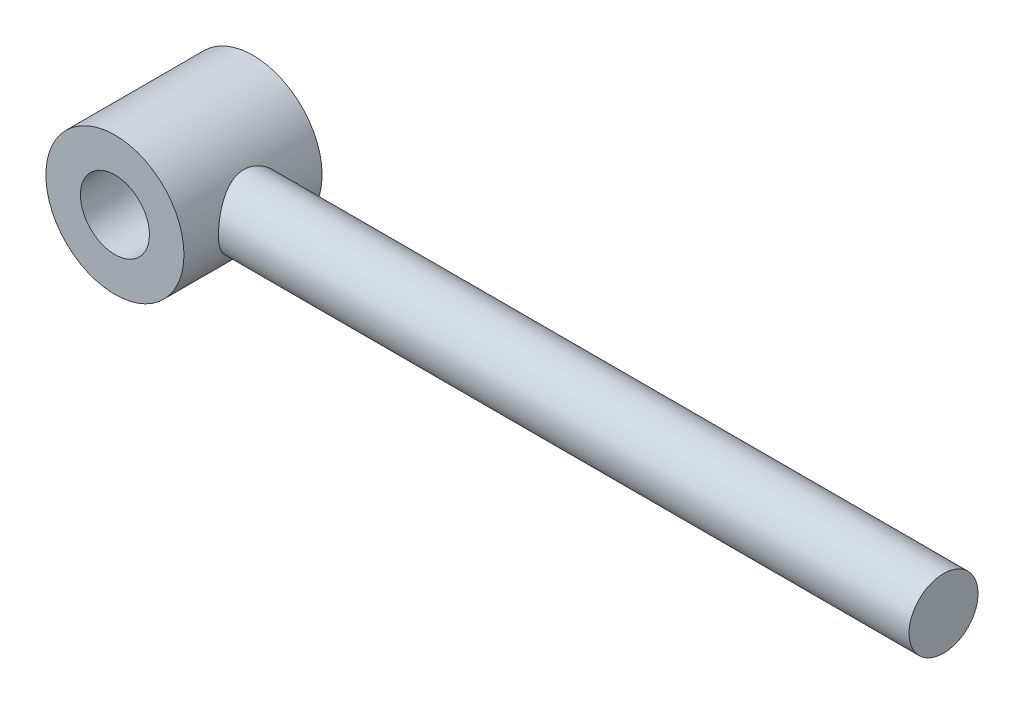
SolidWorks part; units mm, degrees
ref_plane "Piano frontale" through (0, 0, 0) normal (0, 0, 1) x (1, 0, 0)
ref_plane "Piano superiore" through (0, 0, 0) normal (0, 1, 0) x (1, 0, 0)
ref_plane "Piano destro" through (0, 0, 0) normal (1, 0, 0) x (0, 0, -1)
sketch "Schizzo1" plane through (0, 0, 0) normal (0, 0, 1) x (1, 0, 0)
  circle A0 centre (0, 0) radius 10
  circle A1 centre (0, 0) radius 5
  dimension "D1" = 20
  dimension "D2" = 10
extrude "Estrusione-Estrusione1" add sketch "Schizzo1" along normal blind 20
ref_plane "Piano1" through (110, 0, 0) normal (-1, 0, 0) x (0, 0, 1)
sketch "Schizzo2" plane through (110, 0, 0) normal (-1, 0, 0) x (0, 0, 1)
  circle A0 centre (10, 0) radius 5
  point P2 (0, 0)
  point P4 (11.796, 0)
  dimension "D1" = 10
  dimension "D2" = 10
extrude "Estrusione-Estrusione2" add sketch "Schizzo2" along normal up to body separate body
cosmetic thread "Filettatura cosmetica1" parameters "D1"=35, "D2"=8.344
ref_plane "Piano2" through (0, 0, 10) normal (0, 0, 1) x (1, 0, 0)
